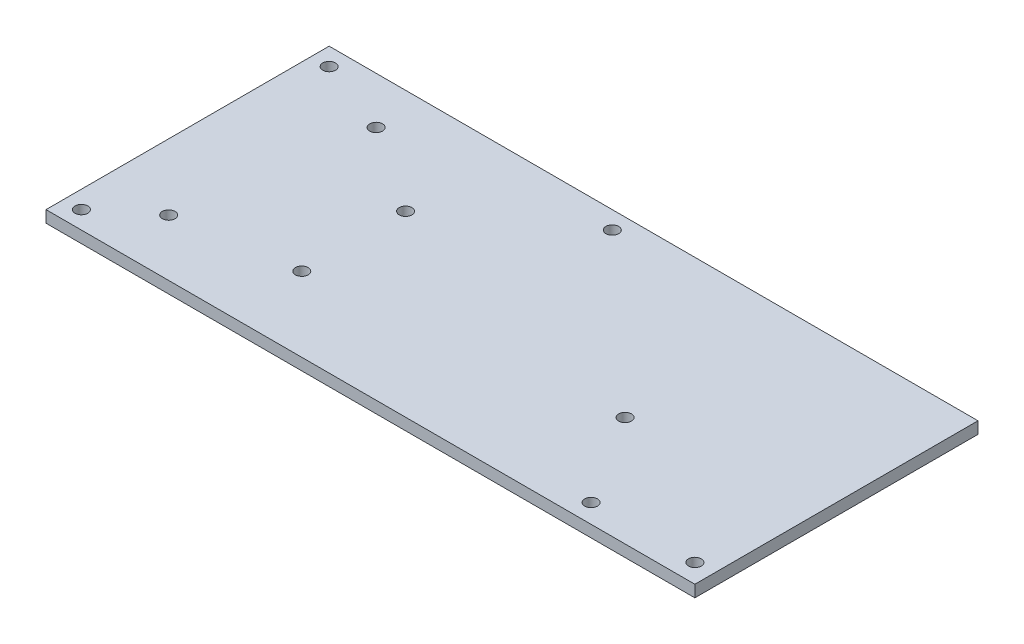
SolidWorks part; units mm, degrees
material "ABS"
ref_plane "Front Plane" through (0, 0, 0) normal (0, 0, 1) x (1, 0, 0)
ref_plane "Top Plane" through (0, 0, 0) normal (0, 1, 0) x (1, 0, 0)
ref_plane "Right Plane" through (0, 0, 0) normal (1, 0, 0) x (0, 0, -1)
sketch "Base Sketch" plane through (0, 0, 0) normal (0, 1, 0) x (1, 0, 0)
  line L1 (-87.3125, -38.1) -> (87.3125, -38.1)
  line L2 (-87.3125, -38.1) -> (-87.3125, 38.1)
  line L3 (-87.3125, 38.1) -> (87.3125, 38.1)
  line L4 (87.3125, -38.1) -> (87.3125, 38.1)
  line L5 (-87.3125, -38.1) -> (87.3125, 38.1) construction
  line L6 (-87.3125, 38.1) -> (87.3125, -38.1) construction
  point P0 (0, 0)
  dimension "D1" = 174.625
  dimension "D2" = 76.2
extrude "Base Plate" add sketch "Base Sketch" along normal blind 3.175
sketch "4-40 Hole Pattern Sketch (Guide Rail)" plane through (0, 3.175, 0) normal (0, 1, 0) x (1, 0, 0)
  line L0 (87.3125, 38.1) -> (-87.3125, 38.1) construction
  line L1 (-87.3125, 38.1) -> (-87.3125, -38.1) construction
  line L2 (-87.3125, -38.1) -> (87.3125, -38.1) construction
  circle A0 centre (-82.55, 33.3375) radius 1.7145
  circle A1 centre (-82.55, -33.3375) radius 1.7145
  circle A2 centre (-6.35, 33.3375) radius 1.7145
  point P0 (-82.55, 33.3375)
  point P5 (-6.35, 33.3375)
  point P6 (-82.55, -33.3375)
  dimension "D7" = 3.429
  dimension "D8" = 3.429
  dimension "D9" = 3.429
  dimension "D1" = 4.7625
  dimension "D2" = 4.7625
  dimension "D3" = 4.7625
  dimension "D4" = 80.9625
  dimension "D5" = 4.7625
  dimension "D6" = 4.7625
sketch "4-40 Hole Pattern Sketch (Arduino Holes)" plane through (0, 3.175, 0) normal (0, 1, 0) x (1, 0, 0)
  line L2 (-87.3125, -38.1) -> (87.3125, -38.1) construction
  line L3 (-87.3125, 38.1) -> (-87.3125, -38.1) construction
  circle A0 centre (-38.5445, -18.034) radius 1.7145
  circle A1 centre (-38.5445, 9.906) radius 1.7145
  circle A6 centre (-69.5325, -22.86) radius 1.7145
  circle A7 centre (-62.0395, 25.4762) radius 1.7145
  dimension "D9" = 4.826
  dimension "D10" = 3.429
  dimension "D11" = 27.94
  dimension "D12" = 30.988
  dimension "D19" = 3.429
  dimension "D20" = 3.429
  dimension "D3" = 15.24
  dimension "D4" = 17.78
  dimension "D5" = 48.3362
  dimension "D6" = 7.493
  dimension "D7" = 3.429
  dimension "D8" = 30.988
extrude "4-40 Guide Rail Holes" cut sketch "4-40 Hole Pattern Sketch (Guide Rail)" against normal up to next
extrude "4-40 Arduino Holes" cut sketch "4-40 Hole Pattern Sketch (Arduino Holes)" against normal up to next
sketch "4-40 Hole Pattern Sketch (IMU Mount)" plane through (0, 3.175, 0) normal (0, 1, 0) x (1, 0, 0)
  line L0 (87.3125, -38.1) -> (87.3125, 38.1) construction
  line L1 (-87.3125, -38.1) -> (87.3125, -38.1) construction
  circle A0 centre (82.2325, -33.02) radius 1.7145
  circle A1 centre (54.2925, -33.02) radius 1.7145
  circle A2 centre (39.0525, -8.636) radius 1.7145
  dimension "D1" = 3.429
  dimension "D2" = 5.08
  dimension "D3" = 5.08
  dimension "D4" = 3.429
  dimension "D5" = 5.08
  dimension "D6" = 27.94
  dimension "D7" = 3.429
  dimension "D8" = 24.384
  dimension "D9" = 43.18
extrude "4-40 IMU Mount Holes" cut sketch "4-40 Hole Pattern Sketch (IMU Mount)" against normal up to next
